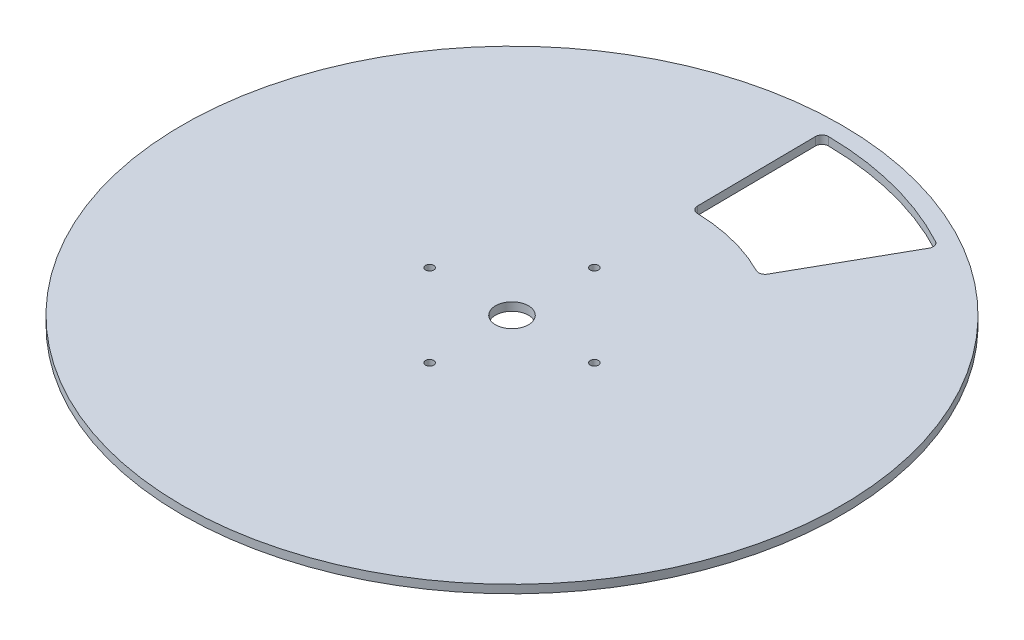
SolidWorks part; units mm, degrees
ref_plane "Front Plane" through (0, 0, 0) normal (0, 0, 1) x (1, 0, 0)
ref_plane "Top Plane" through (0, 0, 0) normal (0, 1, 0) x (1, 0, 0)
ref_plane "Right Plane" through (0, 0, 0) normal (1, 0, 0) x (0, 0, -1)
sketch "Sketch1" plane through (0, 0, 0) normal (0, 1, 0) x (1, 0, 0)
  circle A0 centre (0, 0) radius 127
  dimension "D1" = 254
extrude "Boss-Extrude1" add sketch "Sketch1" along normal blind 3.175
sketch "Sketch2" plane through (0, 3.175, 0) normal (0, 1, 0) x (1, 0, 0)
  circle A0 centre (0, 0) radius 6.35
  dimension "D1" = 12.7
extrude "Cut-Extrude1" cut sketch "Sketch2" against normal through all
sketch "Sketch3" plane through (0, 3.175, 0) normal (0, 1, 0) x (1, 0, 0)
  line L0 (0, 0) -> (-1.2681, 126.9937) construction
  line L1 (0, 0) -> (62.3986, 110.6138) construction
  line L2 (-0.6961, 69.7076) -> (-1.2047, 120.644)
  line L3 (34.3192, 60.8376) -> (59.2211, 104.981)
  circle A0 centre (0, 0) radius 69.85 construction
  circle A1 centre (0, 0) radius 120.65 construction
  circle A2 centre (0, 0) radius 127 construction
  arc A3 (-1.2047, 120.644) -> (59.2211, 104.981) centre (-0.0087, 0.869) cw
  arc A4 (-0.6961, 69.7076) -> (34.3192, 60.8376) centre (0.0105, -1.0515) cw
  dimension "D1" = 139.7
  dimension "D2" = 241.3
  dimension "D3" = 30
extrude "Cut-Extrude2" cut sketch "Sketch3" against normal through all
sketch "Sketch4" plane through (0, 3.175, 0) normal (0, 1, 0) x (1, 0, 0)
  line L0 (0, -31.75) -> (0, 0) construction
  circle A0 centre (0, -31.75) radius 1.5875
  dimension "D1" = 3.175
  dimension "D2" = 31.75
extrude "Cut-Extrude3" cut sketch "Sketch4" against normal through all
pattern_circular "CirPattern1" count 4 over 360 about axis through (0, 0, 0) along (0, 1, 0) of "Cut-Extrude3"
fillet "Fillet1" radius 2.54 4 edges at (-1.2047, 1.5875, -120.644) (59.2211, 1.5875, -104.981) (34.3192, 1.5875, -60.8376) (-0.6961, 1.5875, -69.7076)
